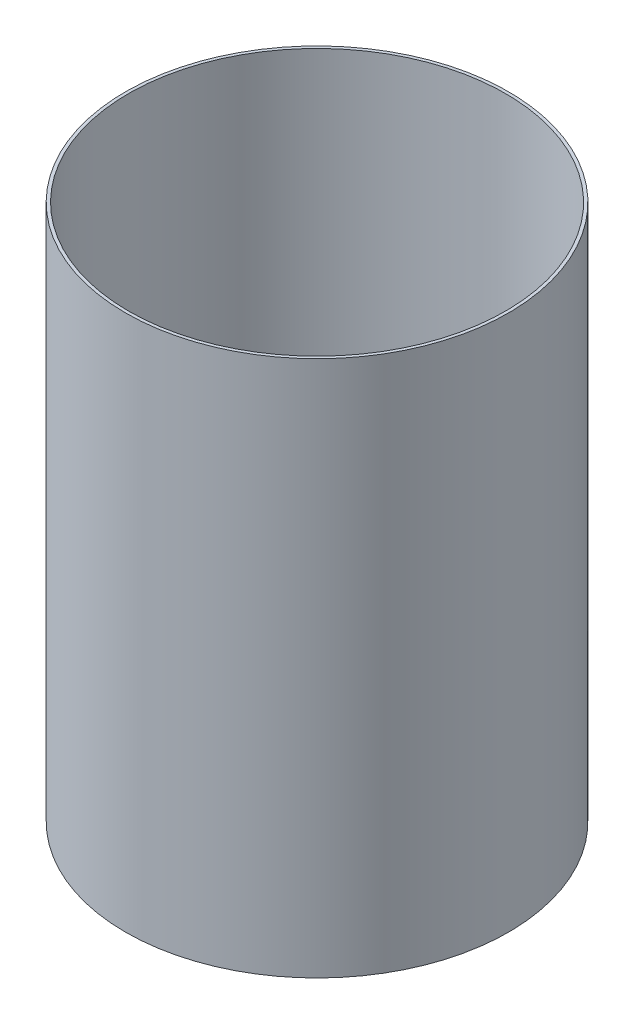
SolidWorks part; units mm, degrees
ref_plane "Front Plane" through (0, 0, 0) normal (0, 0, 1) x (1, 0, 0)
ref_plane "Top Plane" through (0, 0, 0) normal (0, 1, 0) x (1, 0, 0)
ref_plane "Right Plane" through (0, 0, 0) normal (1, 0, 0) x (0, 0, -1)
sketch "Sketch1" plane through (0, 0, 0) normal (0, 1, 0) x (1, 0, 0)
  circle A0 centre (0, 0) radius 62.5
  circle A1 centre (0, 0) radius 61.5
  dimension "D1" = 1
  dimension "D2" = 125
extrude "Boss-Extrude1" add sketch "Sketch1" along normal mid plane 175
